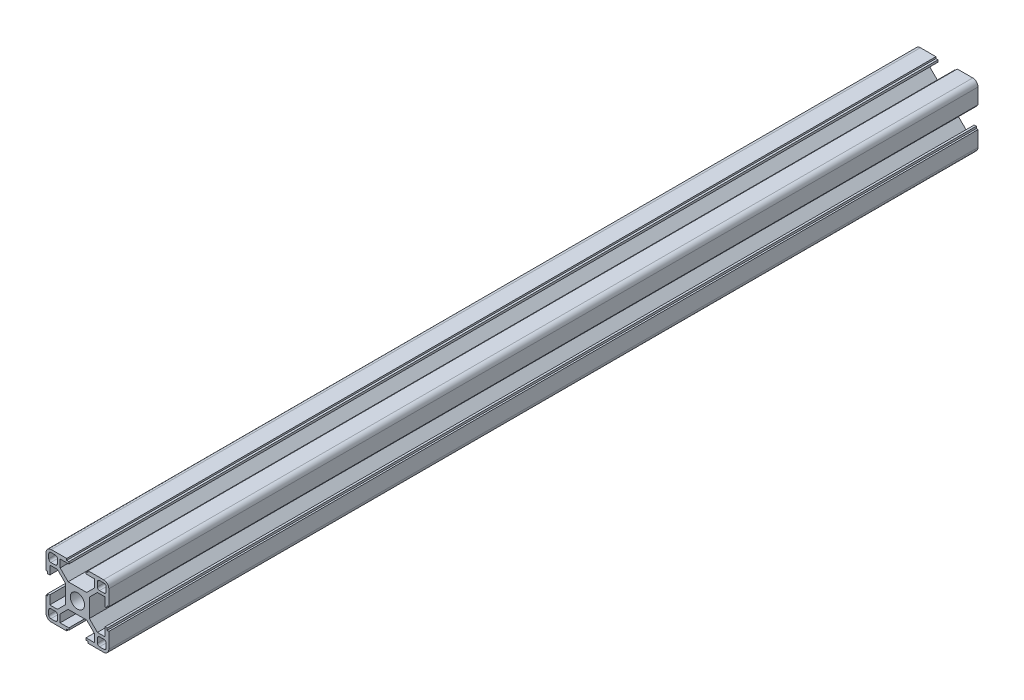
SolidWorks part; units mm, degrees
material "6061-T6 (SS)"
ref_plane "前视基准面" through (0, 0, 0) normal (0, 0, 1) x (1, 0, 0)
ref_plane "上视基准面" through (0, 0, 0) normal (0, 1, 0) x (1, 0, 0)
ref_plane "右视基准面" through (0, 0, 0) normal (1, 0, 0) x (0, 0, -1)
sketch "Sketch1" plane through (0, 0, 0) normal (0, 0, 1) x (1, 0, 0)
  line L0 (-5.1, 15) -> (-5.1, 14.2)
  line L1 (-12.5, -15) -> (12.5, -15)
  line L2 (-15, -12.5) -> (-15, 12.5)
  line L3 (-12.5, 15) -> (12.5, 15)
  line L4 (15, -12.5) -> (15, 12.5)
  line L5 (-15, -15) -> (15, 15) construction
  line L6 (-15, 15) -> (15, -15) construction
  line L7 (-5.1, 14.2) -> (-4.1, 14.2)
  line L8 (-4.1, 14.2) -> (-4.1, 13.2)
  line L9 (-4.1, 13.2) -> (-8.25, 13.2)
  line L10 (-8.25, 13.2) -> (-8.25, 9.5228)
  line L11 (-8.25, 9.5228) -> (-4.4272, 5.7)
  line L12 (-4.4272, 5.7) -> (4.4272, 5.7)
  line L13 (-5.1, 15) -> (5.1, 15)
  line L14 (0, 15) -> (0, 5.7) construction
  line L15 (8.25, 9.5228) -> (4.4272, 5.7)
  line L16 (8.25, 13.2) -> (8.25, 9.5228)
  line L17 (4.1, 13.2) -> (8.25, 13.2)
  line L18 (4.1, 14.2) -> (4.1, 13.2)
  line L19 (5.1, 14.2) -> (4.1, 14.2)
  line L20 (5.1, 15) -> (5.1, 14.2)
  line L21 (15, 5.1) -> (14.2, 5.1)
  line L22 (14.2, 5.1) -> (14.2, 4.1)
  line L23 (14.2, 4.1) -> (13.2, 4.1)
  line L24 (13.2, 4.1) -> (13.2, 8.25)
  line L25 (13.2, 8.25) -> (9.5228, 8.25)
  line L26 (9.5228, 8.25) -> (5.7, 4.4272)
  line L27 (5.7, 4.4272) -> (5.7, -4.4272)
  line L28 (15, 5.1) -> (15, -5.1)
  line L29 (9.5228, -8.25) -> (5.7, -4.4272)
  line L30 (13.2, -8.25) -> (9.5228, -8.25)
  line L31 (13.2, -4.1) -> (13.2, -8.25)
  line L32 (14.2, -4.1) -> (13.2, -4.1)
  line L33 (14.2, -5.1) -> (14.2, -4.1)
  line L34 (15, -5.1) -> (14.2, -5.1)
  line L35 (15, 0) -> (5.7, 0) construction
  line L36 (5.1, -15) -> (5.1, -14.2)
  line L37 (5.1, -14.2) -> (4.1, -14.2)
  line L38 (4.1, -14.2) -> (4.1, -13.2)
  line L39 (4.1, -13.2) -> (8.25, -13.2)
  line L40 (8.25, -13.2) -> (8.25, -9.5228)
  line L41 (8.25, -9.5228) -> (4.4272, -5.7)
  line L42 (4.4272, -5.7) -> (-4.4272, -5.7)
  line L43 (5.1, -15) -> (-5.1, -15)
  line L44 (-8.25, -9.5228) -> (-4.4272, -5.7)
  line L45 (-8.25, -13.2) -> (-8.25, -9.5228)
  line L46 (-4.1, -13.2) -> (-8.25, -13.2)
  line L47 (-4.1, -14.2) -> (-4.1, -13.2)
  line L48 (-5.1, -14.2) -> (-4.1, -14.2)
  line L49 (-5.1, -15) -> (-5.1, -14.2)
  line L50 (0, -15) -> (0, -5.7) construction
  line L51 (-15, -5.1) -> (-14.2, -5.1)
  line L52 (-14.2, -5.1) -> (-14.2, -4.1)
  line L53 (-14.2, -4.1) -> (-13.2, -4.1)
  line L54 (-13.2, -4.1) -> (-13.2, -8.25)
  line L55 (-13.2, -8.25) -> (-9.5228, -8.25)
  line L56 (-9.5228, -8.25) -> (-5.7, -4.4272)
  line L57 (-5.7, -4.4272) -> (-5.7, 4.4272)
  line L58 (-15, -5.1) -> (-15, 5.1)
  line L59 (-9.5228, 8.25) -> (-5.7, 4.4272)
  line L60 (-13.2, 8.25) -> (-9.5228, 8.25)
  line L61 (-13.2, 4.1) -> (-13.2, 8.25)
  line L62 (-14.2, 4.1) -> (-13.2, 4.1)
  line L63 (-14.2, 5.1) -> (-14.2, 4.1)
  line L64 (-15, 5.1) -> (-14.2, 5.1)
  line L65 (-15, 0) -> (-5.7, 0) construction
  line L66 (0, 0) -> (0, 5.7) construction
  circle A0 centre (0, 0) radius 3.4
  arc A1 (-12.5, -15) -> (-15, -12.5) centre (-12.5, -12.5) cw
  arc A2 (12.5, -15) -> (15, -12.5) centre (12.5, -12.5) ccw
  arc A3 (12.5, 15) -> (15, 12.5) centre (12.5, 12.5) cw
  arc A4 (-15, 12.5) -> (-12.5, 15) centre (-12.5, 12.5) cw
  point P0 (0, 0)
  dimension "D3" = 6.8
  dimension "D12" = 2.5
  dimension "D1" = 30
  dimension "D2" = 30
  dimension "D4" = 16.5
  dimension "D5" = 8.2
  dimension "D6" = 10.2
  dimension "D7" = 7.5
  dimension "D9" = 1.8
  dimension "D10" = 1.8
  dimension "D11" = 0.8
  dimension "D8" = 4
extrude "Extrude1" add sketch "Sketch1" along normal blind 415 contours A4 L2 L64 L63 L62 L61 L60 L59 L57 L56 L55 L54 L53 L52 L51 A1 L1 L49 L48 L47 L46 L45 L44 L42 L41 L40 L39 L38 L37 L36 A2 L4 L34 L33 L32 L31 L30 L29 L27 L26 L25 L24 L23 L22 L21 A3 L3 L20
sketch "Sketch2" plane through (0, 0, 415) normal (0, 0, 1) x (1, 0, 0)
  line L0 (13.7, 12.7) -> (13.7, 10.55)
  line L1 (-12.7, 13.7) -> (-10.55, 13.7)
  line L2 (-13.7, 12.7) -> (-13.7, 10.55)
  line L3 (-12.7, 9.55) -> (-10.55, 9.55)
  line L4 (-9.55, 12.7) -> (-9.55, 10.55)
  line L5 (-13.7, 13.7) -> (-9.55, 9.55) construction
  line L6 (-13.7, 9.55) -> (-9.55, 13.7) construction
  line L7 (12.7, 13.7) -> (10.55, 13.7)
  line L8 (9.55, 12.7) -> (9.55, 10.55)
  line L9 (12.7, 9.55) -> (10.55, 9.55)
  line L10 (12.7, -13.7) -> (10.55, -13.7)
  line L11 (13.7, -12.7) -> (13.7, -10.55)
  line L12 (12.7, -9.55) -> (10.55, -9.55)
  line L13 (9.55, -12.7) -> (9.55, -10.55)
  line L14 (-13.7, -12.7) -> (-13.7, -10.55)
  line L15 (-12.7, -13.7) -> (-10.55, -13.7)
  line L16 (-9.55, -12.7) -> (-9.55, -10.55)
  line L17 (-12.7, -9.55) -> (-10.55, -9.55)
  line L18 (0, 0) -> (-9.55, 9.55) construction
  line L19 (-12.5, 15) -> (-5.1, 15) construction
  line L20 (-15, 5.1) -> (-15, 12.5) construction
  line L21 (-13.2, 8.25) -> (-9.5228, 8.25) construction
  line L22 (-8.25, 13.2) -> (-8.25, 9.5228) construction
  arc A0 (-13.7, -12.7) -> (-12.7, -13.7) centre (-12.7, -12.7) ccw
  arc A1 (-10.55, -13.7) -> (-9.55, -12.7) centre (-10.55, -12.7) ccw
  arc A2 (-9.55, -10.55) -> (-10.55, -9.55) centre (-10.55, -10.55) ccw
  arc A3 (-13.7, -10.55) -> (-12.7, -9.55) centre (-12.7, -10.55) cw
  arc A4 (13.7, -10.55) -> (12.7, -9.55) centre (12.7, -10.55) ccw
  arc A5 (12.7, -13.7) -> (13.7, -12.7) centre (12.7, -12.7) ccw
  arc A6 (10.55, -13.7) -> (9.55, -12.7) centre (10.55, -12.7) cw
  arc A7 (10.55, -9.55) -> (9.55, -10.55) centre (10.55, -10.55) ccw
  arc A8 (13.7, 12.7) -> (12.7, 13.7) centre (12.7, 12.7) ccw
  arc A9 (13.7, 10.55) -> (12.7, 9.55) centre (12.7, 10.55) cw
  arc A10 (9.55, 10.55) -> (10.55, 9.55) centre (10.55, 10.55) ccw
  arc A11 (10.55, 13.7) -> (9.55, 12.7) centre (10.55, 12.7) ccw
  arc A12 (-10.55, 13.7) -> (-9.55, 12.7) centre (-10.55, 12.7) cw
  arc A13 (-10.55, 9.55) -> (-9.55, 10.55) centre (-10.55, 10.55) ccw
  arc A14 (-13.7, 10.55) -> (-12.7, 9.55) centre (-12.7, 10.55) ccw
  arc A15 (-12.7, 13.7) -> (-13.7, 12.7) centre (-12.7, 12.7) ccw
  point P0 (-11.625, 11.625)
  dimension "D2" = 1
  dimension "D3" = 1.3
  dimension "D4" = 1.3
  dimension "D5" = 1.3
  dimension "D6" = 1.3
  dimension "D1" = 4
extrude "Extrude2" cut sketch "Sketch2" against normal through all
